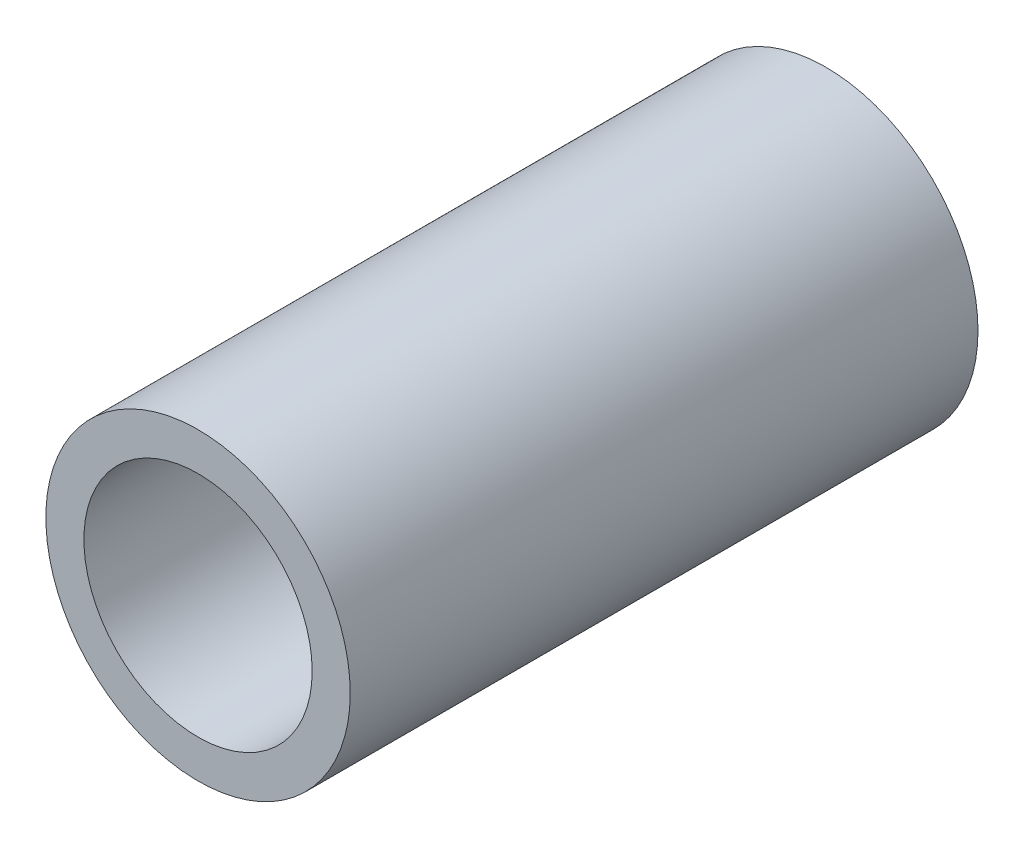
SolidWorks part; units mm, degrees
ref_plane "Ebene vorne" through (0, 0, 0) normal (1, 0, 0) x (0, 1, 0)
ref_plane "Ebene oben" through (0, 0, 0) normal (0, 0, 1) x (0, 1, 0)
ref_plane "Ebene rechts" through (0, 0, 0) normal (0, 1, 0) x (-1, 0, 0)
sketch "Skizze1" plane through (0, 0, 0) normal (0, 0, 1) x (0, 1, 0)
  circle A0 centre (0, 0) radius 4
  circle A1 centre (0, 0) radius 3
  dimension "D1" = 8
  dimension "D2" = 6
extrude "Aufsatz-Linear austragen1" add sketch "Skizze1" along normal blind 16.5
